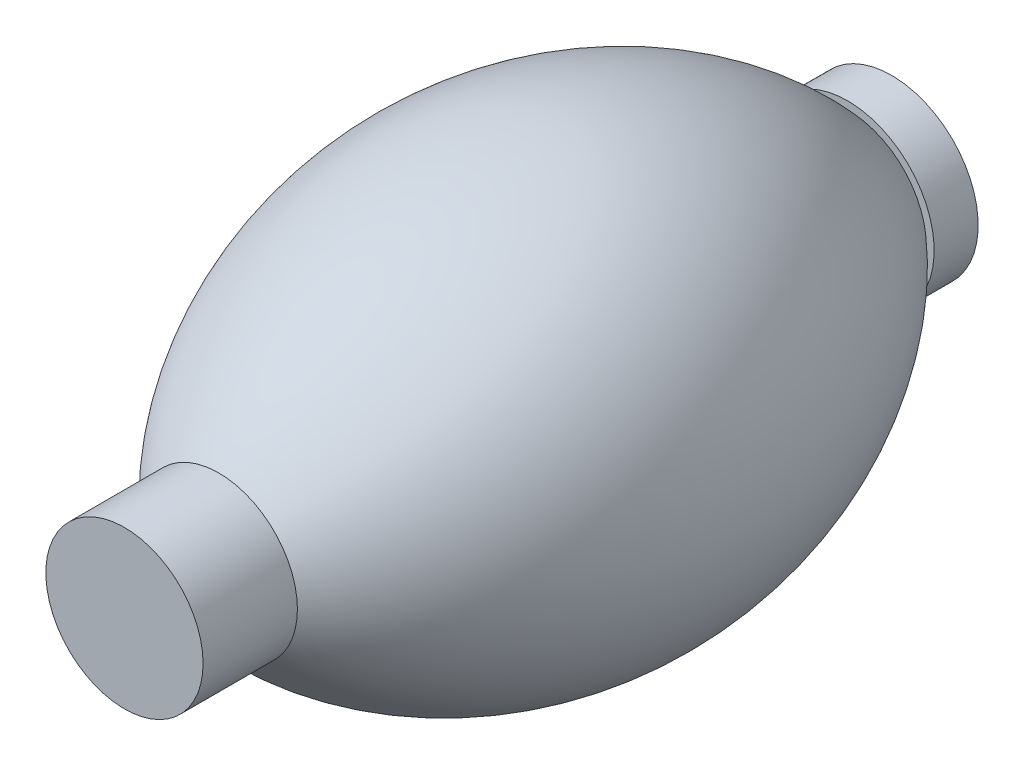
SolidWorks part; units mm, degrees
ref_plane "Front Plane" through (0, 0, 0) normal (0, 0, 1) x (1, 0, 0)
ref_plane "Top Plane" through (0, 0, 0) normal (0, 1, 0) x (1, 0, 0)
ref_plane "Right Plane" through (0, 0, 0) normal (1, 0, 0) x (0, 0, -1)
sketch "Sketch1" plane through (0, 0, 0) normal (1, 0, 0) x (0, 0, -1)
  line L0 (-74.1179, 0) -> (97.1498, 0) construction
  line L1 (-100, 0) -> (-100, 25)
  line L5 (100, 25) -> (100, 0)
  line L6 (-100, 0) -> (100, 0)
  arc A1 (-100, 25) -> (100, 25) centre (0, -63.5489) cw
  dimension "D3" = 133.5699
  dimension "D1" = 25
  dimension "D2" = 25
  dimension "D5" = 100
  dimension "D6" = 100
revolve "Revolve1" add sketch "Sketch1" angle 360 about L0
sketch "Sketch2" plane through (0, 0, 100) normal (0, 0, 1) x (1, 0, 0)
  circle A0 centre (0, 0) radius 25
  dimension "D1" = 50
extrude "Boss-Extrude1" add sketch "Sketch2" along normal blind 30
sketch "Sketch3" plane through (0, 0, -100) normal (0, 0, -1) x (-1, 0, 0)
  circle A0 centre (0, 0) radius 27.5
  dimension "D1" = 55
extrude "Boss-Extrude2" add sketch "Sketch3" along normal blind 14
